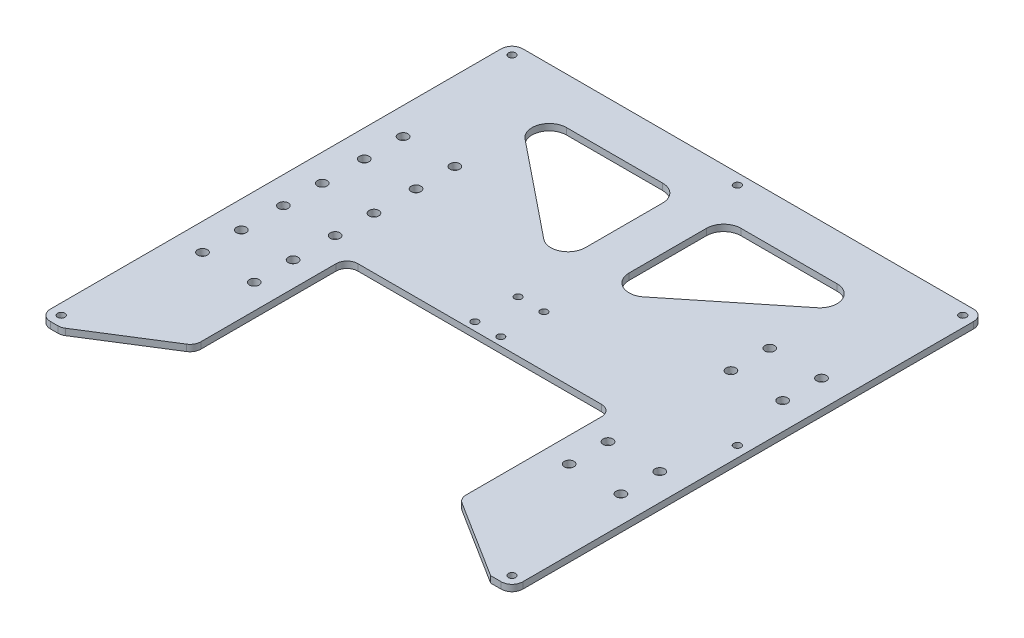
SolidWorks part; units mm, degrees
ref_plane "Front Plane" through (0, 0, 0) normal (0, 0, 1) x (1, 0, 0)
ref_plane "Top Plane" through (0, 0, 0) normal (0, 1, 0) x (1, 0, 0)
ref_plane "Right Plane" through (0, 0, 0) normal (1, 0, 0) x (0, 0, -1)
sketch "Sketch1" plane through (0, 0, 0) normal (0, 1, 0) x (1, 0, 0)
  line L0 (-99.5871, -109.5) -> (-61.5, -85.534)
  line L1 (-109.5, -109.5) -> (-99.5871, -109.5)
  line L2 (-109.5, -109.5) -> (-109.5, 109.5)
  line L3 (-109.5, 109.5) -> (109.5, 109.5)
  line L4 (109.5, -109.5) -> (109.5, 109.5)
  line L5 (-35.4632, 0) -> (38.6341, 0) construction
  line L6 (-104.5, 104.5) -> (104.5, 104.5) construction
  line L9 (99.5871, -109.5) -> (109.5, -109.5)
  line L10 (0, 0) -> (0, 35.1029) construction
  line L11 (-97, 9) -> (-73, 9) construction
  line L12 (-97, -9) -> (-73, -9) construction
  line L13 (-97, 9) -> (-97, -9) construction
  line L14 (-97, 46.5) -> (-73, 46.5) construction
  line L15 (-97, 28.5) -> (-73, 28.5) construction
  line L16 (-97, 46.5) -> (-97, 28.5) construction
  line L17 (-97, -46.5) -> (-97, -28.5) construction
  line L18 (-97, -28.5) -> (-73, -28.5) construction
  line L19 (-97, -46.5) -> (-73, -46.5) construction
  line L20 (73, -46.5) -> (97, -46.5) construction
  line L21 (-61.5, -85.534) -> (-61.5, -15)
  line L22 (-61.5, -15) -> (61.5, -15)
  line L23 (61.5, -15) -> (61.5, -85.534)
  line L24 (99.5871, -109.5) -> (61.5, -85.534)
  line L25 (-10.1471, 80.0056) -> (-10.1471, 44.1415)
  line L26 (-23.1625, 37.9088) -> (-67.7309, 73.7729)
  line L27 (-62.7155, 88.0056) -> (-18.1471, 88.0056)
  line L28 (10.1471, 80.0056) -> (10.1471, 44.1415)
  line L29 (23.1625, 37.9088) -> (67.7309, 73.7729)
  line L30 (62.7155, 88.0056) -> (18.1471, 88.0056)
  circle A0 centre (-104.5, 104.5) radius 1.7
  circle A1 centre (104.5, 104.5) radius 1.7
  circle A2 centre (104.5, -104.5) radius 1.7
  circle A3 centre (-104.5, -104.5) radius 1.7
  circle A4 centre (-97, 9) radius 2.25
  circle A5 centre (-73, 9) radius 2.25
  circle A6 centre (-73, -9) radius 2.25
  circle A7 centre (-97, -9) radius 2.25
  circle A8 centre (-97, 46.5) radius 2.25
  circle A9 centre (-73, 46.5) radius 2.25
  circle A10 centre (-73, 28.5) radius 2.25
  circle A11 centre (-97, 28.5) radius 2.25
  circle A12 centre (-97, -28.5) radius 2.25
  circle A13 centre (-73, -28.5) radius 2.25
  circle A14 centre (-73, -46.5) radius 2.25
  circle A15 centre (-97, -46.5) radius 2.25
  circle A16 centre (73, -46.5) radius 2.25
  circle A17 centre (97, -46.5) radius 2.25
  circle A18 centre (73, -28.5) radius 2.25
  circle A19 centre (97, -28.5) radius 2.25
  circle A20 centre (73, 28.5) radius 2.25
  circle A21 centre (97, 28.5) radius 2.25
  circle A22 centre (73, 46.5) radius 2.25
  circle A23 centre (97, 46.5) radius 2.25
  circle A24 centre (0, 104.5) radius 1.7
  circle A25 centre (104.5, 0) radius 1.7
  circle A26 centre (-6, 8.8158) radius 1.65
  circle A27 centre (6, 8.8158) radius 1.65
  circle A28 centre (6, -11.1842) radius 1.65
  circle A29 centre (-6, -11.1842) radius 1.65
  arc A30 (67.7309, 73.7729) -> (62.7155, 88.0056) centre (62.7155, 80.0056) ccw
  arc A31 (10.1471, 44.1415) -> (23.1625, 37.9088) centre (18.1471, 44.1415) ccw
  arc A32 (10.1471, 80.0056) -> (18.1471, 88.0056) centre (18.1471, 80.0056) cw
  arc A33 (-10.1471, 44.1415) -> (-23.1625, 37.9088) centre (-18.1471, 44.1415) cw
  arc A34 (-18.1471, 88.0056) -> (-10.1471, 80.0056) centre (-18.1471, 80.0056) cw
  arc A35 (-67.7309, 73.7729) -> (-62.7155, 88.0056) centre (-62.7155, 80.0056) cw
  point P0 (0, 0)
  point P11 (109.5, 0)
  point P12 (0, 109.5)
  point P23 (0, 104.5)
  point P34 (-85, 9)
  point P35 (-85, -9)
  point P36 (-97, 0)
  point P45 (-85, 46.5)
  point P46 (-85, 28.5)
  point P48 (-85, -46.5)
  point P49 (85, -46.5)
  point P79 (0, -15)
  point P96 (85.4179, 88.0056)
  point P99 (10.1471, 27.4354)
  point P102 (10.1471, 88.0056)
  point P105 (-10.1471, 27.4354)
  point P108 (-10.1471, 88.0056)
  point P111 (-85.4179, 88.0056)
  dimension "D5" = 4.5
  dimension "D12" = 3.4
  dimension "D16" = 12
  dimension "D18" = 3.3
  dimension "D19" = 8
  dimension "D1" = 219
  dimension "D2" = 219
  dimension "D3" = 209
  dimension "D4" = 209
  dimension "D6" = 24
  dimension "D7" = 18
  dimension "D8" = 24
  dimension "D9" = 18
  dimension "D10" = 57
  dimension "D11" = 170
  dimension "D13" = 94.5
  dimension "D14" = 48
  dimension "D15" = 45
  dimension "D17" = 20
extrude "Boss-Extrude1" add sketch "Sketch1" along normal blind 3
fillet "Fillet1" radius 5 9 edges at (-99.5871, 1.5, 109.5) (109.5, 1.5, 109.5) (-109.5, 1.5, 109.5) (109.5, 1.5, -109.5) (-109.5, 1.5, -109.5) (61.5, 1.5, 85.534) (61.5, 1.5, 15) (-61.5, 1.5, 15) (-61.5, 1.5, 85.534)
